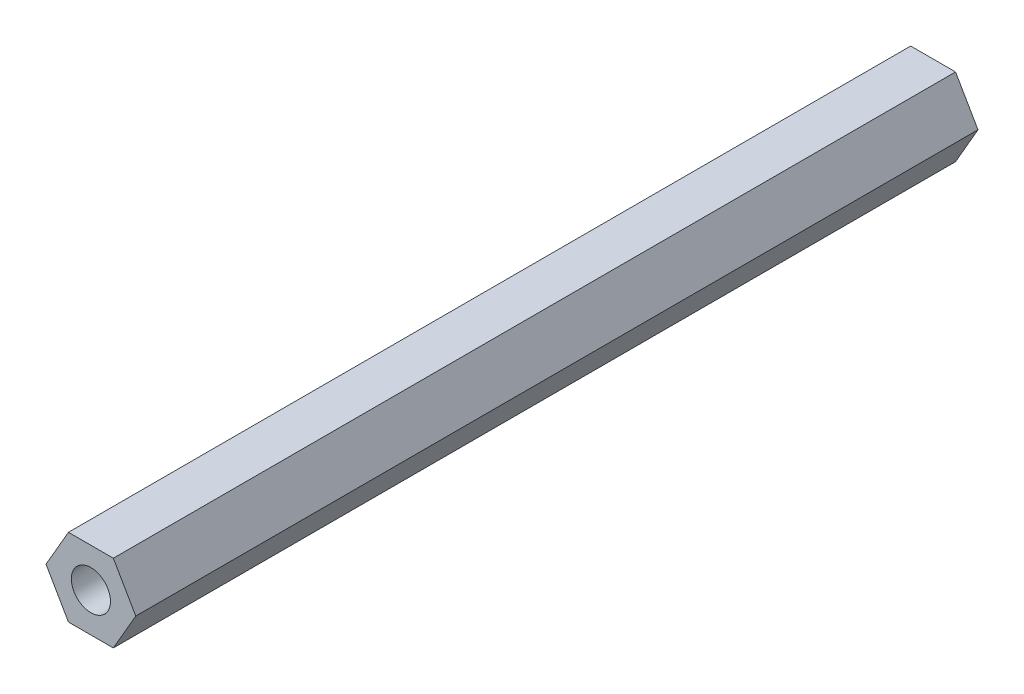
SolidWorks part; units mm, degrees
material "黄铜"
ref_plane "前视基准面" through (0, 0, 0) normal (0, 0, 1) x (1, 0, 0)
ref_plane "上视基准面" through (0, 0, 0) normal (0, 1, 0) x (1, 0, 0)
ref_plane "右视基准面" through (0, 0, 0) normal (1, 0, 0) x (0, 0, -1)
other "Configuration Table"
sketch "六角对边与轴向孔" plane through (0, 0, 0) normal (0, 0, 1) x (1, 0, 0)
  line L0 (3.4641, 0) -> (1.7321, 3)
  line L1 (1.7321, 3) -> (-1.7321, 3)
  line L2 (-1.7321, 3) -> (-3.4641, 0)
  line L3 (-3.4641, 0) -> (-1.7321, -3)
  line L4 (-1.7321, -3) -> (1.7321, -3)
  line L5 (1.7321, -3) -> (3.4641, 0)
extrude "隔柱高度_70mm" add sketch "六角对边与轴向孔" along normal blind 65
sketch "底端_M3内牙轮廓" plane through (0, 0, 0) normal (0, 0, -1) x (-1, 0, 0)
  circle A0 centre (0, 0) radius 1.51
extrude "底端_M3内牙" cut sketch "底端_M3内牙轮廓" against normal blind 8
sketch "顶端_M3内牙轮廓" plane through (0, 0, 65) normal (0, 0, 1) x (1, 0, 0)
  circle A0 centre (0, 0) radius 1.51
extrude "顶端_M3内牙" cut sketch "顶端_M3内牙轮廓" against normal blind 8
